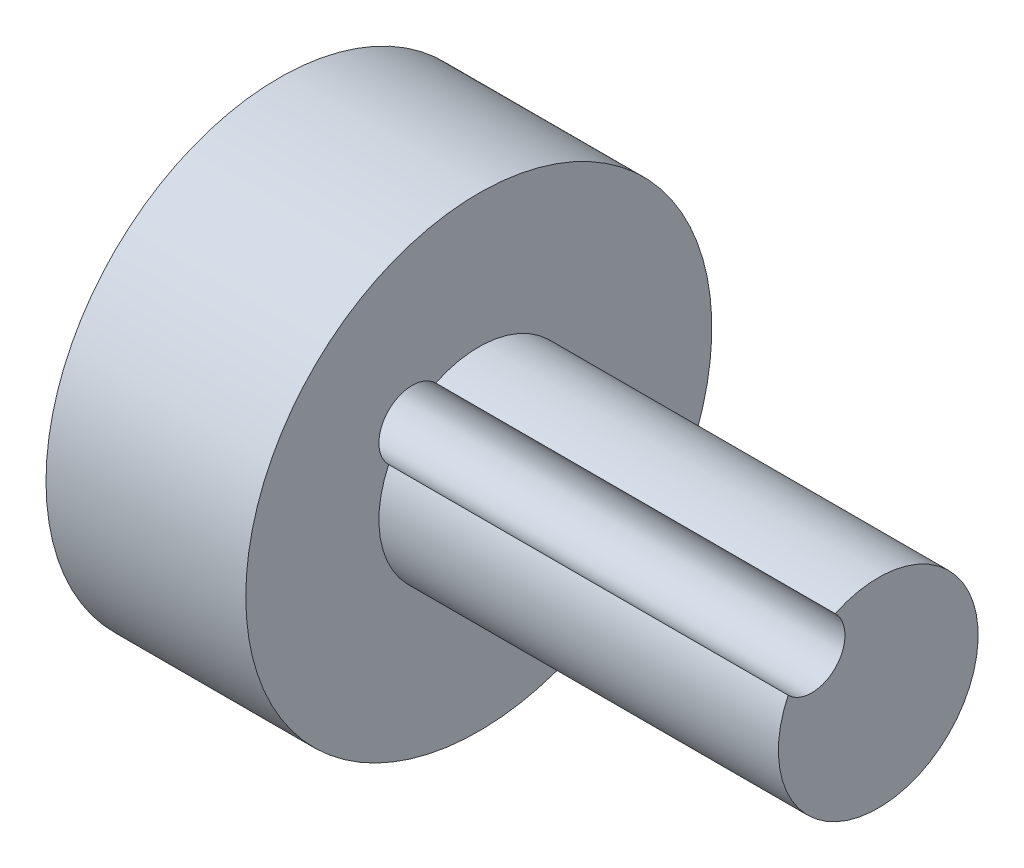
SolidWorks part; units mm, degrees
ref_plane "Спереди" through (0, 0, 0) normal (0, 0, 1) x (1, 0, 0)
ref_plane "Сверху" through (0, 0, 0) normal (0, 1, 0) x (1, 0, 0)
ref_plane "Справа" through (0, 0, 0) normal (1, 0, 0) x (0, 0, -1)
sketch "Эскиз1" plane through (0, 0, 0) normal (0, 0, 1) x (1, 0, 0)
  line L0 (0, 0) -> (100, 0)
  line L1 (0, 0) -> (0, 20)
  line L2 (0, 20) -> (10, 20)
  line L3 (10, 20) -> (10, 35)
  line L4 (10, 35) -> (40, 35)
  line L5 (40, 35) -> (40, 15)
  line L6 (40, 15) -> (100, 15)
  line L7 (100, 0) -> (100, 15)
revolve "Повернуть1" add sketch "Эскиз1" angle 360 about L0
sketch "Эскиз2" plane through (0, 0, 0) normal (1, 0, 0) x (0, 0, -1)
  circle A0 centre (10, 10) radius 5
extrude "Вырез-Вытянуть1" cut sketch "Эскиз2" along normal blind 20
sketch "Эскиз3" plane through (0, 0, 0) normal (1, 0, 0) x (0, 0, -1)
  circle A0 centre (-10, 10) radius 5
extrude "Вырез-Вытянуть2" cut sketch "Эскиз3" along normal through all
